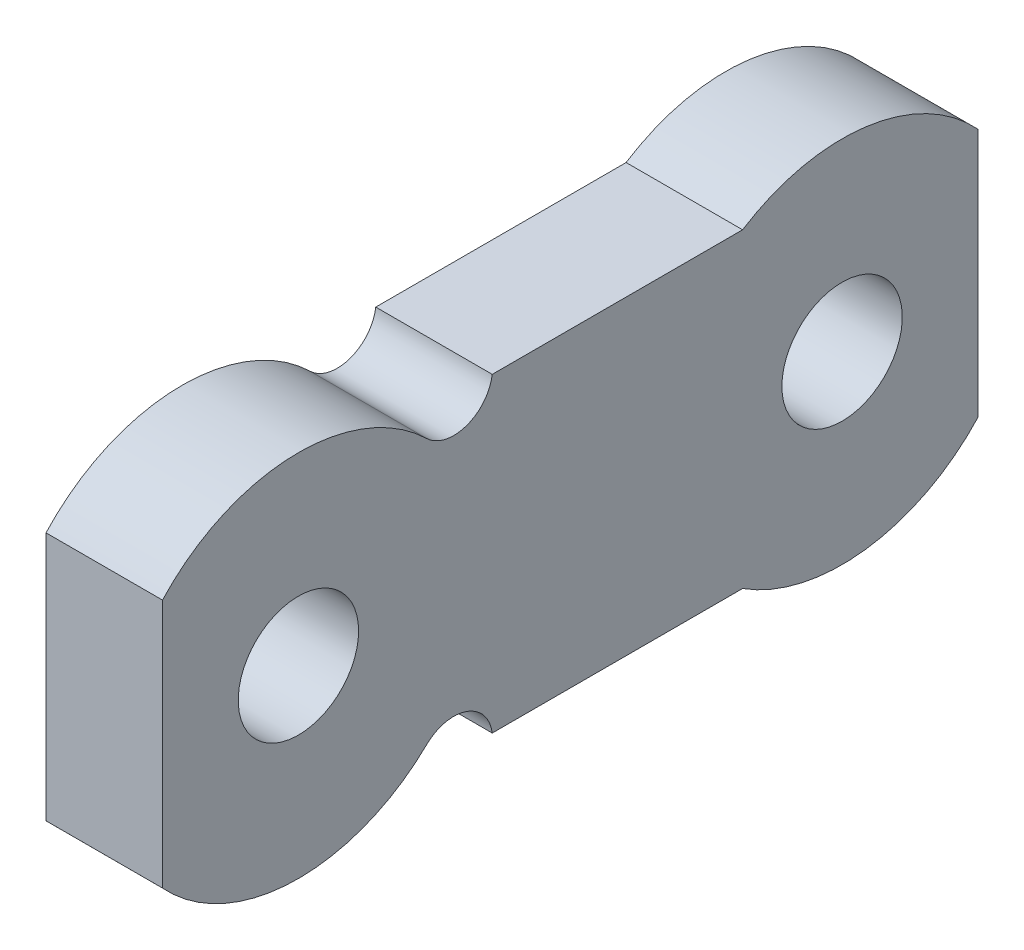
SolidWorks part; units mm, degrees
material "Thornel Mat VMA"
ref_plane "前视基准面" through (0, 0, 0) normal (0, 0, 1) x (1, 0, 0)
ref_plane "上视基准面" through (0, 0, 0) normal (0, 1, 0) x (1, 0, 0)
ref_plane "右视基准面" through (0, 0, 0) normal (1, 0, 0) x (0, 0, -1)
sketch "草图1" plane through (0, 0, 0) normal (1, 0, 0) x (0, 0, -1)
  line L0 (-7, 0) -> (0, 0) construction
  line L1 (0, 0) -> (0, 8.3036) construction
  line L4 (-2.0086, 4) -> (4.4383, 4)
  line L5 (-2.0086, -4) -> (4.4383, -4)
  line L6 (-10.5, 3.2113) -> (-10.5, -3.2113)
  line L7 (10.5, 3.2113) -> (10.5, -3.2113)
  circle A0 centre (-7, 0) radius 1.55
  circle A1 centre (7, 0) radius 1.55
  arc A2 (-3.6957, 3.4123) -> (-10.5, 3.2113) centre (-7, 0) ccw
  arc A3 (4.4383, -4) -> (10.5, -3.2113) centre (7, 0) ccw
  arc A4 (-3.6957, 3.4123) -> (-2.0086, 4) centre (-3, 4.1307) ccw
  arc A5 (-3.6957, -3.4123) -> (-2.0086, -4) centre (-3, -4.1307) cw
  circle A6 centre (-7, 0) radius 3 construction
  arc A7 (-10.5, -3.2113) -> (-3.6957, -3.4123) centre (-7, 0) ccw
  arc A8 (10.5, 3.2113) -> (4.4383, 4) centre (7, 0) ccw
  dimension "D1" = 14
  dimension "D2" = 3.1
  dimension "D3" = 9.5
  dimension "D6" = 2
  dimension "D7" = 6
  dimension "D4" = 8
  dimension "D5" = 3
  dimension "D8" = 3.5
extrude "凸台-拉伸1" add sketch "草图1" along normal blind 3
